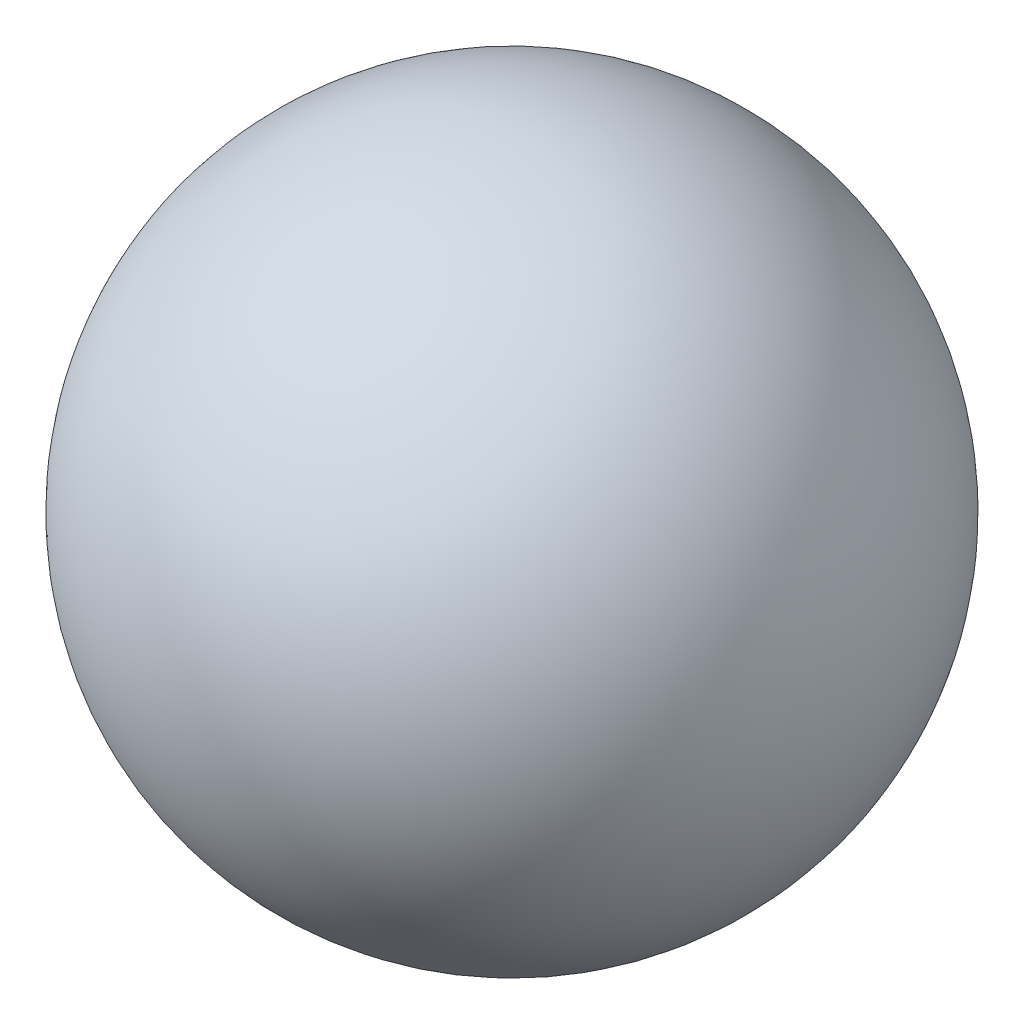
SolidWorks part; units mm, degrees
ref_plane "Спереди" through (0, 0, 0) normal (0, 0, 1) x (1, 0, 0)
ref_plane "Сверху" through (0, 0, 0) normal (0, 1, 0) x (1, 0, 0)
ref_plane "Справа" through (0, 0, 0) normal (1, 0, 0) x (0, 0, -1)
sketch "Sketch2" plane through (0, 0, 0) normal (0, 0, 1) x (1, 0, 0)
  line L0 (-12, 0) -> (12, 0)
  arc A0 (12, 0) -> (-12, 0) centre (0, 0) cw
  dimension "D1" = 24
revolve "Revolve1" add sketch "Sketch2" angle 360 about L0
